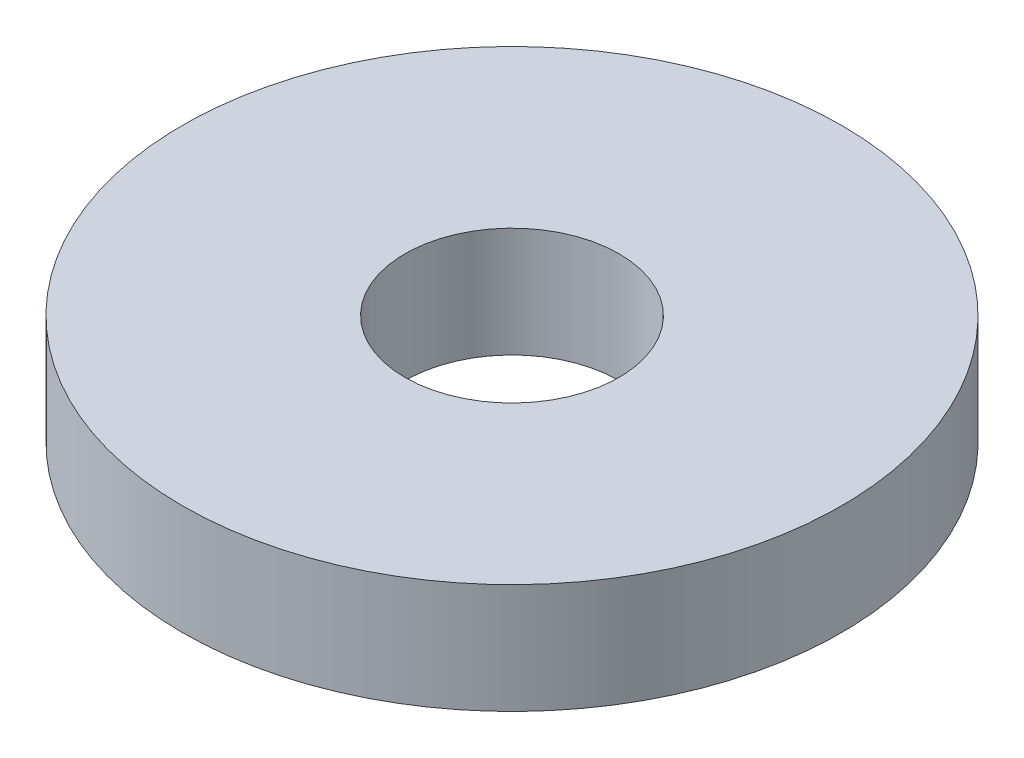
SolidWorks part; units mm, degrees
ref_plane "Plano frontal" through (0, 0, 0) normal (0, 0, 1) x (1, 0, 0)
ref_plane "Plano superior" through (0, 0, 0) normal (0, 1, 0) x (1, 0, 0)
ref_plane "Plano direito" through (0, 0, 0) normal (1, 0, 0) x (0, 0, -1)
sketch "Esboço1" plane through (0, 0, 0) normal (0, 1, 0) x (1, 0, 0)
  circle A0 centre (0, 0) radius 6
  circle A1 centre (0, 0) radius 1.95
  dimension "D1" = 12
  dimension "D2" = 3.9
extrude "Ressalto-extrusão1" add sketch "Esboço1" along normal blind 2
